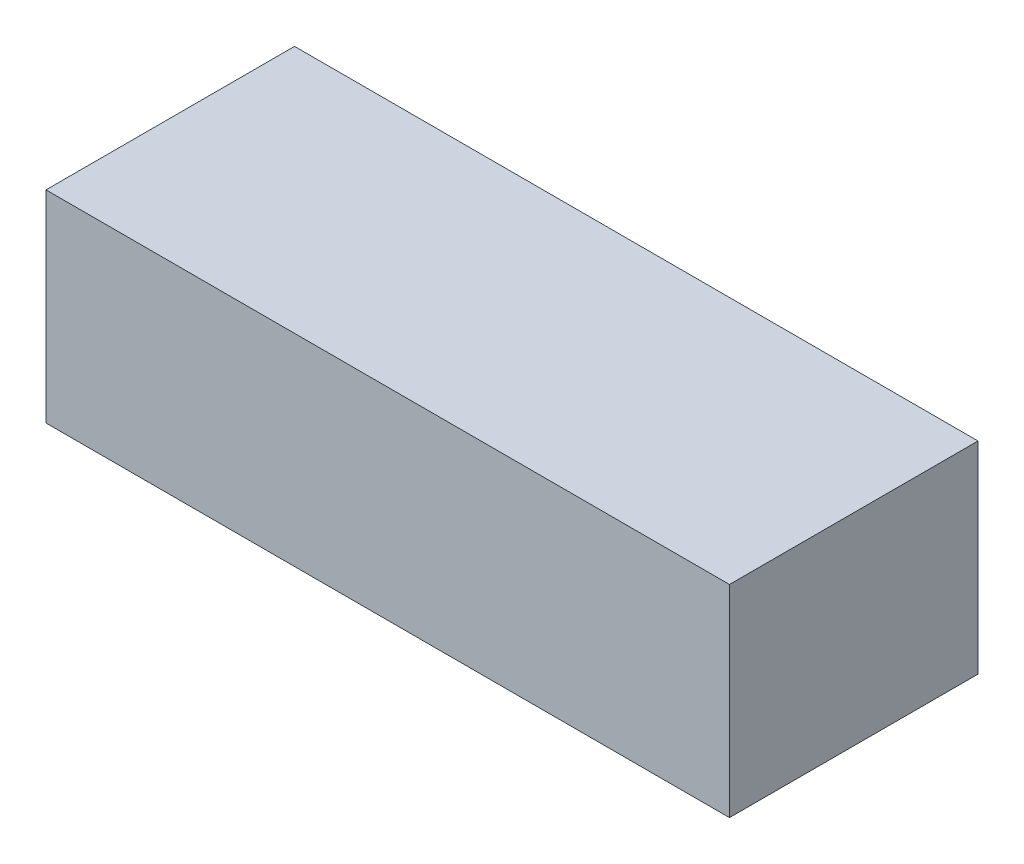
SolidWorks part; units mm, degrees
ref_plane "前视基准面" through (0, 0, 0) normal (0, 0, 1) x (1, 0, 0)
ref_plane "上视基准面" through (0, 0, 0) normal (0, 1, 0) x (1, 0, 0)
ref_plane "右视基准面" through (0, 0, 0) normal (1, 0, 0) x (0, 0, -1)
sketch "草图1" plane through (0, 0, 0) normal (0, 1, 0) x (1, 0, 0)
  line L1 (-22, 8) -> (22, 8)
  line L2 (-22, 8) -> (-22, -8)
  line L3 (-22, -8) -> (22, -8)
  line L4 (22, 8) -> (22, -8)
  line L5 (-22, 8) -> (22, -8) construction
  line L6 (-22, -8) -> (22, 8) construction
  point P0 (0, 0)
extrude "凸台-拉伸1" add sketch "草图1" against normal blind 2 contours L2 L1 L4 L3
sketch "草图2" plane through (0, -2, 0) normal (0, -1, 0) x (1, 0, 0)
  line L0 (-22, -8) -> (-22, 8) construction
  line L1 (-20, 6) -> (20, 6)
  line L2 (-20, 6) -> (-20, -6)
  line L3 (-20, -6) -> (20, -6)
  line L4 (20, 6) -> (20, -6)
  line L5 (-22, 8) -> (22, 8) construction
  line L6 (-22, -8) -> (22, -8) construction
  line L7 (22, -8) -> (22, 8) construction
  line L8 (-22, -8) -> (-22, 8)
  line L9 (-22, 8) -> (22, 8)
  line L10 (-22, -8) -> (22, -8)
  line L11 (22, -8) -> (22, 8)
  dimension "D1" = 12
  dimension "D2" = 40
  dimension "D3" = 2
  dimension "D4" = 2
extrude "凸台-拉伸2" add sketch "草图2" along normal blind 10
sketch "草图3" plane through (-22, 0, 0) normal (-1, 0, 0) x (0, 0, 1)
  line L0 (0, 0) -> (0, -12)
  line L1 (-5.5, -7) -> (5.5, -7)
  line L2 (-5.5, -7) -> (-5.5, -11)
  line L3 (-5.5, -11) -> (5.5, -11)
  line L4 (5.5, -7) -> (5.5, -11)
  line L5 (-5.5, -7) -> (5.5, -11) construction
  line L6 (-5.5, -11) -> (5.5, -7) construction
  line L7 (8, -12) -> (-8, -12) construction
  line L8 (-8, 0) -> (8, 0) construction
  point P0 (0, -9)
  dimension "D1" = 4
  dimension "D2" = 11
  dimension "D3" = 7
extrude "切除-拉伸1" cut sketch "草图3" against normal blind 2 contours L4 L1 L0 L3 | L2 L3 L0 L1
sketch "草图4" plane through (0, -2, 0) normal (0, -1, 0) x (1, 0, 0)
  line L0 (-20, -6) -> (20, -6) construction
  line L1 (-20, 6) -> (8, 6)
  line L2 (-20, 6) -> (-20, -6)
  line L3 (-20, -6) -> (8, -6)
  line L4 (8, 6) -> (8, -6)
  line L5 (20, -6) -> (20, 6) construction
  line L6 (-5.15, 6) -> (-6.85, 6)
  line L7 (-20, 6) -> (-18.3, 6)
  line L8 (-20, 6) -> (-20, -6)
  line L9 (-20, -6) -> (-18.3, -6)
  line L10 (-18.3, 6) -> (-18.3, -6)
  line L11 (8, 6) -> (6.3, 6)
  line L12 (8, 6) -> (8, -6)
  line L13 (8, -6) -> (6.3, -6)
  line L14 (6.3, 6) -> (6.3, -6)
  line L15 (-5.15, 6) -> (-5.15, -6)
  line L16 (-5.15, -6) -> (-6.85, -6)
  line L17 (-6.85, 6) -> (-6.85, -6)
  point P17 (0, 0)
  point P18 (0, 0)
  line M6 (-20, -6) -> (20, -6)
  line M8 (20, 6) -> (-20, 6)
  dimension "D1" = 12
  dimension "D2" = 1.7
  dimension "D3" = 1.7
  dimension "D4" = 0
  dimension "D5" = 24.6
  dimension "D6" = 11.45
  dimension "D7" = 11.45
extrude "凸台-拉伸4" add sketch "草图4" along normal blind 4.6 contours L14 L4 M8 M6 | L8 L7 L10 L9 | L6 L17 L16 L15
sketch "草图9" plane through (0, -12, 0) normal (0, -1, 0) x (1, 0, 0)
  line L0 (-22, 8) -> (-22, -8) construction
  line L1 (21, -7) -> (-21, -7)
  line L2 (21, -7) -> (21, 7)
  line L3 (21, 7) -> (-21, 7)
  line L4 (-21, -7) -> (-21, 7)
  line L5 (21, -7) -> (-21, 7) construction
  line L6 (21, 7) -> (-21, -7) construction
  line L7 (22, 8) -> (-22, 8) construction
  line L8 (22, -8) -> (22, 8) construction
  line L9 (-22, -8) -> (22, -8) construction
  line L10 (22, -8) -> (22, 8)
  line L11 (-22, -8) -> (22, -8)
  line L12 (-22, 8) -> (-22, -8)
  line L13 (22, 8) -> (-22, 8)
  point P0 (0, 0)
  dimension "D1" = 1
  dimension "D2" = 1
extrude "凸台-拉伸5" add sketch "草图9" along normal blind 1
sketch "草图11" plane through (0, -12, 0) normal (0, -1, 0) x (1, 0, 0)
  line L7 (-20, -6) -> (20, -6) construction
  line L8 (-20, -6) -> (21, -6)
  line L9 (21, -7) -> (21, 7) construction
  point P1 (21, -6)
  point P3 (21, -6)
sketch "草图12" plane through (0, -12, 0) normal (0, -1, 0) x (1, 0, 0)
  line L1 (20, 6) -> (21, 6)
  line L2 (20, 6) -> (20, -6)
  line L3 (20, -6) -> (21, -6)
  line L4 (21, 6) -> (21, -6)
extrude "切除-拉伸3" cut sketch "草图12" against normal blind 5
